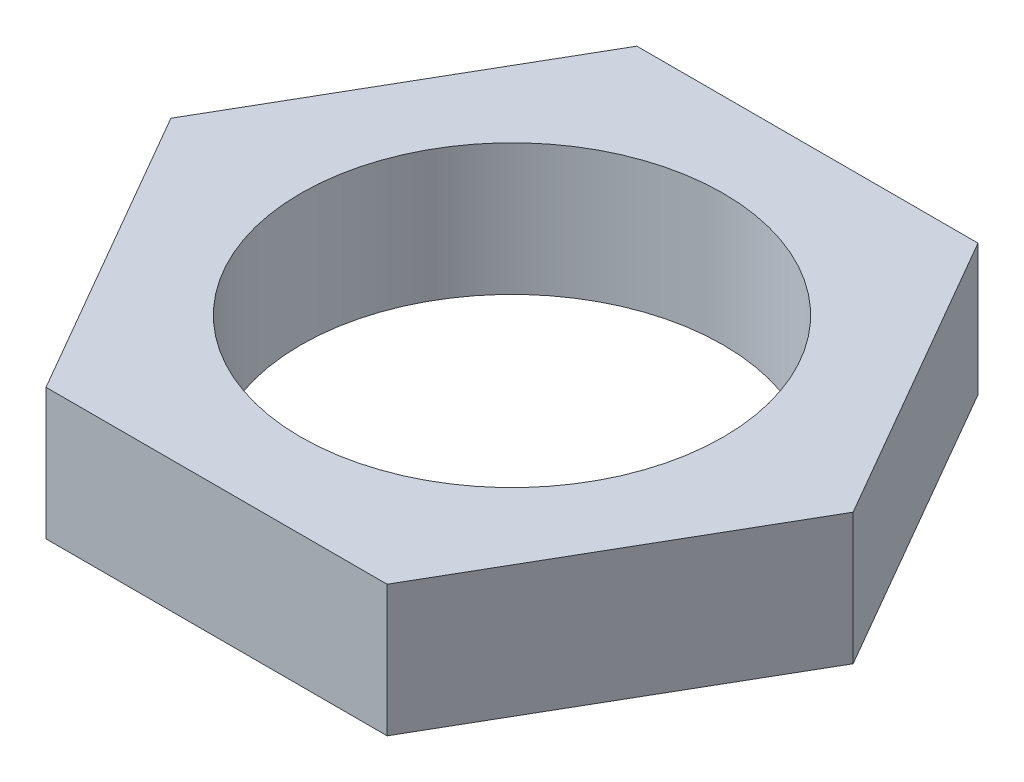
SolidWorks part; units mm, degrees
material "PE haute densité"
ref_plane "Plan de face" through (0, 0, 0) normal (0, 0, 1) x (1, 0, 0)
ref_plane "Plan de dessus" through (0, 0, 0) normal (0, 1, 0) x (1, 0, 0)
ref_plane "Plan de droite" through (0, 0, 0) normal (1, 0, 0) x (0, 0, -1)
sketch "Esquisse1" plane through (0, 0, 0) normal (0, 1, 0) x (1, 0, 0)
  line L1 (7.7942, -13.5) -> (15.5885, 0)
  line L2 (15.5885, 0) -> (7.7942, 13.5)
  line L3 (7.7942, 13.5) -> (-7.7942, 13.5)
  line L4 (-7.7942, 13.5) -> (-15.5885, 0)
  line L5 (-15.5885, 0) -> (-7.7942, -13.5)
  line L6 (-7.7942, -13.5) -> (7.7942, -13.5)
  circle A0 centre (0, 0) radius 13.5 construction
  circle A1 centre (0, 0) radius 9.65
  dimension "D2" = 19.3
  dimension "D1" = 27
extrude "Extrusion1" add sketch "Esquisse1" along normal blind 6
